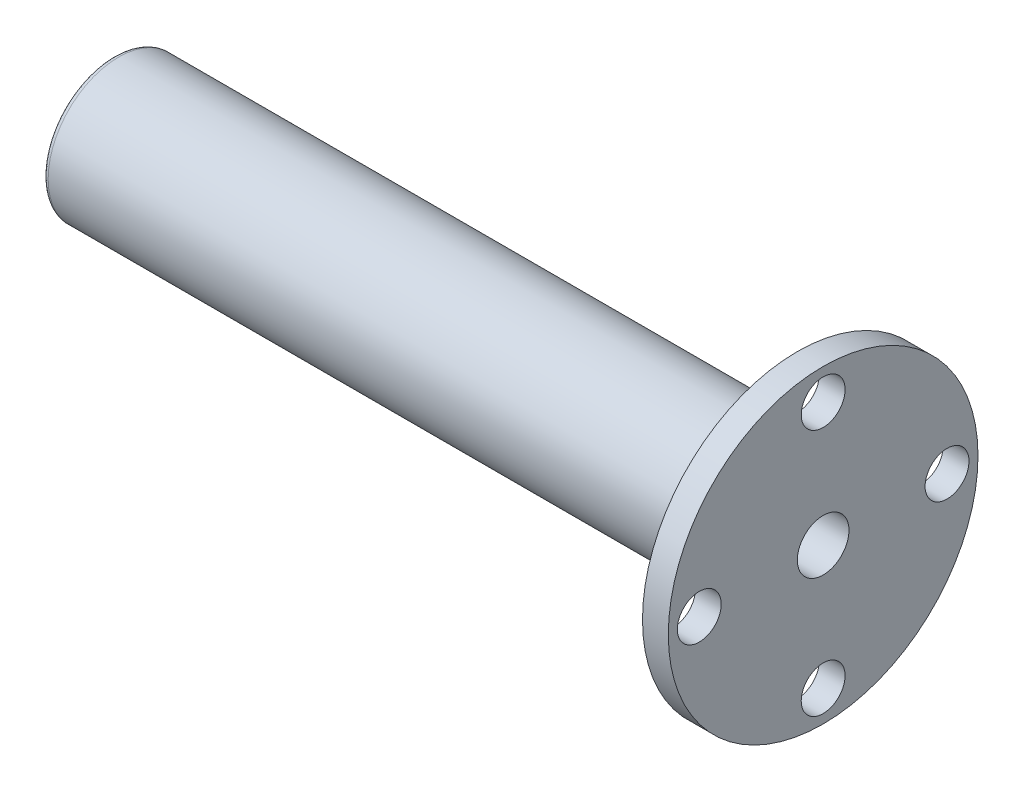
SolidWorks part; units mm, degrees
ref_plane "Plan de face" through (0, 0, 0) normal (0, 0, 1) x (1, 0, 0)
ref_plane "Plan de dessus" through (0, 0, 0) normal (0, 1, 0) x (1, 0, 0)
ref_plane "Plan de droite" through (0, 0, 0) normal (1, 0, 0) x (0, 0, -1)
sketch "Esquisse1" plane through (0, 0, 0) normal (0, 0, 1) x (1, 0, 0)
  line L0 (-75.0544, 0) -> (199.9456, 0)
  line L1 (199.9456, 0) -> (199.9456, 60)
  line L2 (199.9456, 60) -> (189.9456, 60)
  line L3 (189.9456, 60) -> (189.9456, 27.3)
  line L4 (189.9456, 27.3) -> (-75.0544, 27.3)
  line L5 (-75.0544, 27.3) -> (-75.0544, 0)
  dimension "D1" = 265
  dimension "D2" = 10
  dimension "D3" = 60
  dimension "D4" = 27.3
revolve "Révolution1" add sketch "Esquisse1" angle 360 about L0
sketch "Esquisse2" plane through (199.9456, 0, 0) normal (1, 0, 0) x (0, 0, -1)
  line L0 (0, 48) -> (0, 0)
  line L1 (0, 0) -> (-48, 0)
  circle A0 centre (0, 0) radius 48
  circle A1 centre (0, 48) radius 8.5
  circle A2 centre (0, -48) radius 8.5
  circle A3 centre (-48, 0) radius 8.5
  circle A4 centre (48, 0) radius 8.5
  circle A5 centre (0, 0) radius 10
  circle A6 centre (0, 0) radius 5
  dimension "D1" = 96
  dimension "D2" = 17
  dimension "D3" = 17
  dimension "D4" = 20
  dimension "D5" = 10
extrude "Enlèv. mat.-Extru.1" cut sketch "Esquisse2" against normal blind 25 contours A2 | A4 | A3 | A1 | A5
sketch "Esquisse3" plane through (174.9456, 0, 0) normal (1, 0, 0) x (0, 0, -1)
  circle A0 centre (0, 0) radius 5
  dimension "D1" = 10
extrude "Enlèv. mat.-Extru.2" cut sketch "Esquisse3" against normal blind 113.6
fillet "Congé1" radius 2 1 edges at (-75.0544, 0, 27.3)
sketch "Esquisse4" plane through (0, 0, 0) normal (0, 1, 0) x (1, 0, 0)
  line L0 (-89.9756, 0) -> (199.9456, 0)
  line L1 (199.9456, -60) -> (199.9456, 60) construction
  line L2 (59.4456, 106.5802) -> (59.4456, -89.3899)
  line L3 (199.9456, 106.5802) -> (199.9456, -100.8501)
  circle A0 centre (59.4456, 0) radius 5
  dimension "D2" = 10
  dimension "D1" = 140.5
extrude "Enlèv. mat.-Extru.3" cut sketch "Esquisse4" against normal blind 105.5 and the other way blind 5 contours A0
